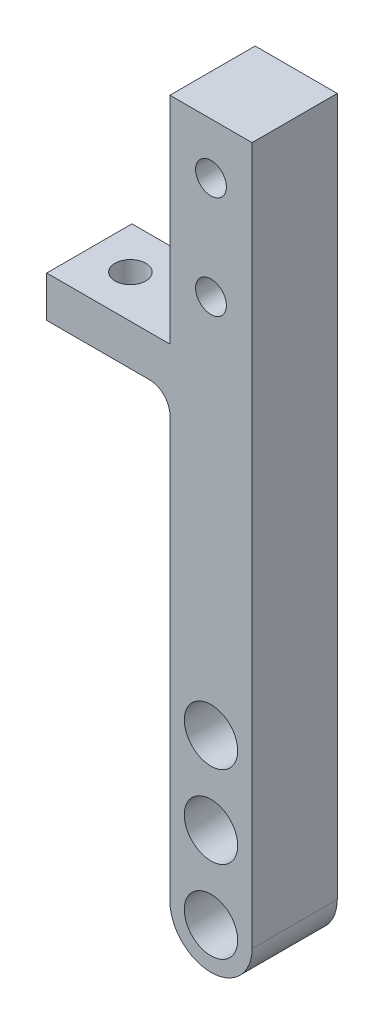
SolidWorks part; units mm, degrees
ref_plane "Alzado" through (0, 0, 0) normal (0, 0, 1) x (1, 0, 0)
ref_plane "Planta" through (0, 0, 0) normal (0, 1, 0) x (1, 0, 0)
ref_plane "Vista lateral" through (0, 0, 0) normal (1, 0, 0) x (0, 0, -1)
sketch "Croquis1" plane through (0, 0, 0) normal (0, 0, 1) x (1, 0, 0)
  line L0 (-18.4906, -1024.48) -> (-18.4906, -1040.48) construction
  line L1 (-14.4906, -1037.6044) -> (-14.4906, -1040.48)
  line L2 (-22.4906, -1024.48) -> (-22.4906, -1040.48)
  line L3 (-22.4906, -1024.48) -> (-22.4906, -997.48)
  line L4 (-14.4906, -1037.6044) -> (-14.4906, -972.48)
  line L5 (-22.4906, -997.48) -> (-34.4906, -997.48)
  line L6 (-22.4906, -997.48) -> (-22.4906, -1040.48)
  line L7 (-22.4906, -993.48) -> (-34.4906, -993.48)
  line L8 (-34.4906, -993.48) -> (-34.4906, -997.48)
  line L12 (-22.4906, -1040.48) -> (-22.4906, -972.48)
  line L13 (-22.4906, -972.48) -> (-14.4906, -972.48)
  circle A0 centre (-18.4906, -1024.48) radius 2.6
  circle A1 centre (-18.4906, -1032.48) radius 2.6
  circle A2 centre (-18.4906, -1040.48) radius 2.6
  arc A4 (-22.4906, -1040.48) -> (-14.4906, -1040.48) centre (-18.4906, -1040.48) ccw
  circle A5 centre (-18.4906, -977.48) radius 1.5
  circle A6 centre (-18.4906, -987.48) radius 1.5
  point P9 (-18.4906, -1032.48)
  dimension "D1" = 5.2
  dimension "D2" = 4
  dimension "D8" = 3
  dimension "D3" = 4
  dimension "D4" = 43
  dimension "D5" = 68
  dimension "D6" = 8
  dimension "D7" = 12
  dimension "D9" = 4
  dimension "D10" = 10
  dimension "D11" = 5
extrude "Saliente-Extruir1" add sketch "Croquis1" along normal mid plane 8.3
sketch "Croquis2" plane through (0, -993.48, 0) normal (0, 1, 0) x (1, 0, 0)
  line L0 (-22.4906, -4.15) -> (-22.4906, 4.15) construction
  line L1 (-22.4906, -4.15) -> (-34.4906, -4.15) construction
  circle A0 centre (-30.4906, 0) radius 1.5
  dimension "D2" = 3
  dimension "D3" = 4.15
  dimension "D1" = 8
extrude "Cortar-Extruir1" cut sketch "Croquis2" against normal blind 10
fillet "Redondeo2" radius 2 1 edges at (-22.4906, -997.48, 0)
